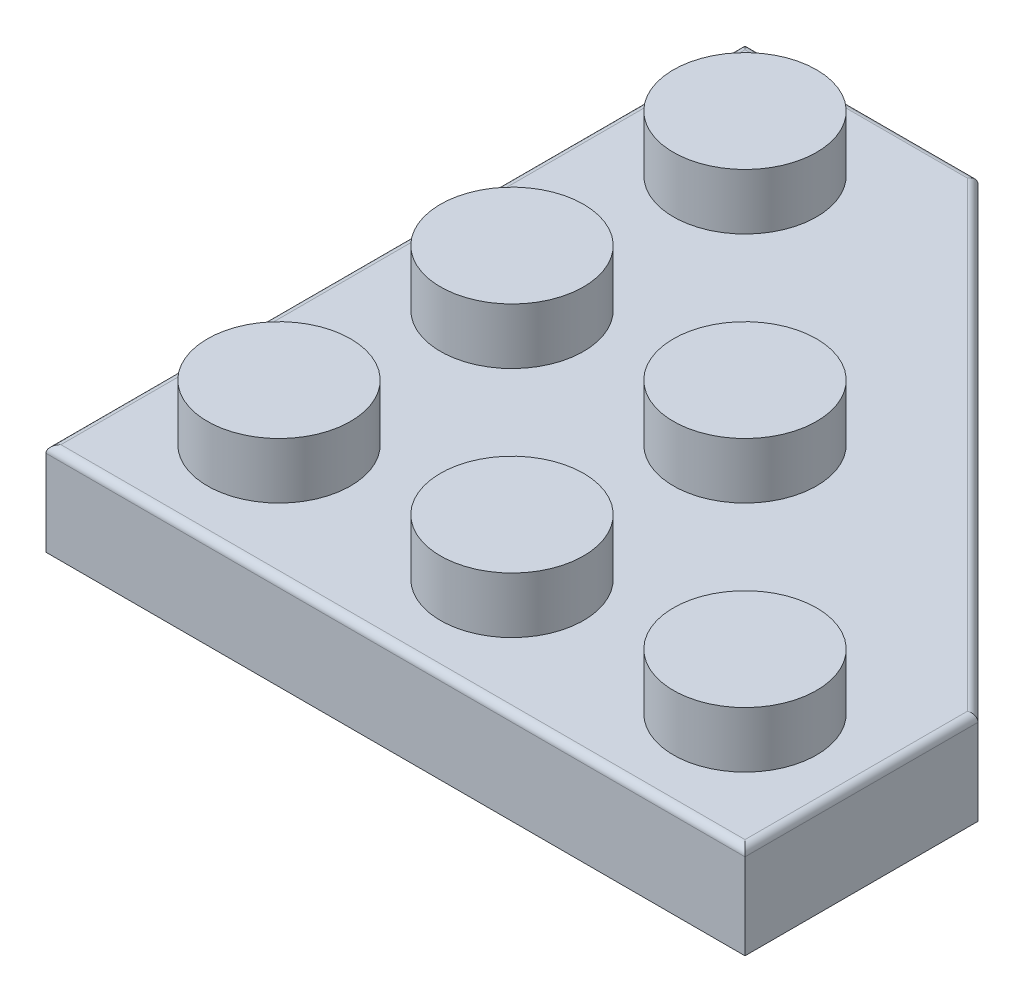
SolidWorks part; units mm, degrees
ref_plane "Front" through (0, 0, 0) normal (0, 0, 1) x (1, 0, 0)
ref_plane "Top" through (0, 0, 0) normal (0, 1, 0) x (1, 0, 0)
ref_plane "Right" through (0, 0, 0) normal (1, 0, 0) x (0, 0, -1)
sketch "Sketch1" plane through (0, 0, 0) normal (0, 1, 0) x (1, 0, 0)
  line L0 (0, 0) -> (0, 50.4571) construction
  line L1 (0, 0) -> (55.8847, 0) construction
  line L2 (-11.9062, 11.9062) -> (11.9062, 11.9062)
  line L3 (-11.9062, 11.9062) -> (-11.9062, -11.9062)
  line L4 (11.9062, -11.9062) -> (-11.9062, -11.9062)
  line L5 (11.9062, -11.9062) -> (11.9062, 11.9062)
  dimension "Length" = 23.8125
  dimension "Width" = 23.8125
extrude "Base-Extrude" add sketch "Sketch1" along normal blind 3.175
sketch "Sketch2" plane through (0, 3.175, 0) normal (0, 1, 0) x (-1, 0, 0)
  line L0 (11.9062, -11.9062) -> (11.9062, 11.9062) construction
  line L1 (-11.9062, 11.9062) -> (11.9062, 11.9062) construction
  circle A0 centre (7.9375, 7.9375) radius 2.4384
  dimension "DotDiam" = 4.8768
  dimension "DotLSpc" = 3.9688
  dimension "DotWSpc" = 3.9688
extrude "Boss-Extrude1" add sketch "Sketch2" along normal blind 1.905
pattern_linear "LPattern4" count 3 spacing 7.9375 along (1, 0, 0) count 3 spacing 7.9375 along (0, 0, -1) skipping (1, 2), (2, 1), (2, 2) of "Boss-Extrude1"
sketch "Sketch4" plane through (0, 3.175, 0) normal (0, 1, 0) x (-1, 0, 0)
  line L0 (-11.9062, 3.9688) -> (3.9688, -11.9062)
  line L1 (-11.9062, 11.9062) -> (-11.9062, -11.9062) construction
  line L2 (11.9062, -11.9062) -> (-11.9062, -11.9062) construction
  line L3 (3.9688, -11.9062) -> (-11.9062, -11.9062)
  line L4 (-11.9062, -11.9062) -> (-11.9062, 3.9688)
  line L5 (-11.9062, 11.9062) -> (11.9062, 11.9062) construction
  dimension "D1" = 7.9375
extrude "Cut-Extrude1" cut sketch "Sketch4" against normal through all
shell "Shell1" thickness 1.5875
sketch "Sketch3" plane through (0, 1.5875, 0) normal (0, -1, 0) x (1, 0, 0)
  line L1 (0, 0) -> (-7.9375, -7.9375) construction
  circle A0 centre (-3.9688, -3.9688) radius 2.4384
  dimension "InsDotDiam" = 4.8768
extrude "InsDot" add sketch "Sketch3" along normal up to surface (1.5875 mm away) thin
sketch "Sketch5" plane through (-0.9184, 1.5875, 6.872) normal (0, -1, 0) x (1, 0, 0)
  line L1 (0.9184, 1.0655) -> (-7.0191, -6.872) construction
  circle A0 centre (-3.0503, -2.9033) radius 2.4384
  dimension "InsDotDiam" = 4.8768
extrude "Boss-Extrude-Thin1" add sketch "Sketch5" along normal up to surface (1.5875 mm away) thin
sketch "Sketch6" plane through (7.7015, 1.5875, 8.8989) normal (0, -1, 0) x (1, 0, 0)
  line L1 (0.236, -0.9614) -> (-7.7015, -8.8989) construction
  circle A0 centre (-3.7327, -4.9301) radius 2.4384
  dimension "InsDotDiam" = 4.8768
extrude "Boss-Extrude-Thin2" add sketch "Sketch6" along normal up to surface (1.5875 mm away) thin
sketch "Sketch7" plane through (0, 0, 0) normal (0, -1, 0) x (1, 0, 0)
  line L0 (0, 0) -> (7.4612, -7.4612) construction
  line L1 (5.5403, -0.1521) -> (6.6628, -1.2747)
  line L2 (10.3187, 4.6263) -> (-4.6263, -10.3187) construction
  line L3 (11.9063, 3.9688) -> (-3.9688, -11.9062) construction
  line L4 (6.6628, -1.2747) -> (10.0753, 2.1378)
  line L5 (10.0753, 2.1378) -> (8.9528, 3.2604)
  line L6 (8.9528, 3.2604) -> (5.5403, -0.1521)
  line L7 (-3.2604, -8.9528) -> (0.1521, -5.5403)
  line L8 (-2.1378, -10.0753) -> (-3.2604, -8.9528)
  line L9 (1.2747, -6.6628) -> (-2.1378, -10.0753)
  line L10 (0.1521, -5.5403) -> (1.2747, -6.6628)
  dimension "D1" = 4.826
  dimension "D2" = 3.81
extrude "Cut-Extrude2" cut sketch "Sketch7" against normal up to surface (1.5875 mm away)
sketch "Sketch8" plane through (0, 0, 0) normal (0, -1, 0) x (1, 0, 0)
  line L0 (0, 0) -> (6.3186, -6.3186) construction
  line L1 (6.6628, -1.2747) -> (1.2747, -6.6628) construction
  line L2 (2.8881, -2.8881) -> (1.9901, -1.9901)
  dimension "D1" = 1.27
extrude "Boss-Extrude-Thin3" add sketch "Sketch8" against normal up to next thin thin type mid plane wall 1
fillet "Fillet1" radius 0.254 5 edges at (11.9062, 3.175, 7.9375) (-7.9375, 3.175, -11.9062) (3.9688, 3.175, -3.9688) (-11.9062, 3.175, 0) (0, 3.175, 11.9062)
equation "\"WdotSpc@LPattern4\" = \"LdotSpc@LPattern4\""
